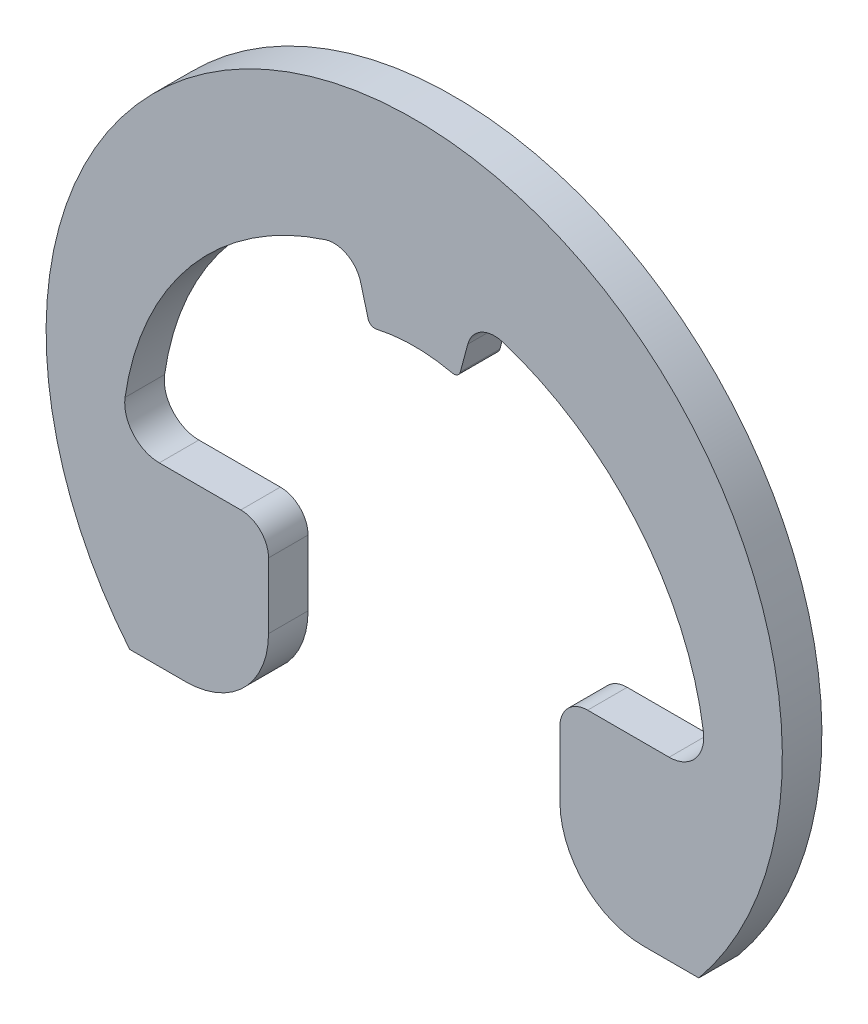
SolidWorks part; units mm, degrees
ref_plane "Front Plane" through (0, 0, 0) normal (0, 0, 1) x (1, 0, 0)
ref_plane "Top Plane" through (0, 0, 0) normal (0, 1, 0) x (1, 0, 0)
ref_plane "Right Plane" through (0, 0, 0) normal (1, 0, 0) x (0, 0, -1)
sketch "Sketch1" plane through (0, 0, 0) normal (0, 0, 1) x (1, 0, 0)
  circle A0 centre (0, 0) radius 8.375 construction
  circle A1 centre (0, 0) radius 3.9 construction
  point P3 (-8.375, 0)
  dimension "Ring OD" = 16.75
  dimension "ID" = 7.8
sketch "Sketch2" plane through (0, 0, 0) normal (0, 1, 0) x (1, 0, 0)
  line L0 (0, -0.45) -> (0, 0.45) construction
  line L1 (-8.375, -0.45) -> (0, -0.45) construction
  line L2 (-8.375, -0.45) -> (-8.375, 0.45) construction
  line L3 (-8.375, 0.45) -> (0, 0.45) construction
  point P2 (0, 0)
  dimension "Ring Thickness" = 0.9
sketch "Sketch3" plane through (0, 0, 0) normal (0, 1, 0) x (1, 0, 0)
  line L0 (-8.375, -0.45) -> (-8.375, 0.45)
  line L1 (0, 0.45) -> (0, -0.45)
  line L2 (-8.375, -0.45) -> (0, -0.45)
  line L3 (-8.375, 0.45) -> (0, 0.45)
revolve "Revolve1" add sketch "Sketch3" angle 360 about L1
sketch "Sketch4" plane through (0, 0, 0) normal (0, 0, 1) x (1, 0, 0)
  line L0 (1.0094, 3.7671) -> (1.7528, 6.5416) construction
  line L1 (-1.0094, 3.7671) -> (-1.7528, 6.5416) construction
  line L2 (-3.315, -2.0545) -> (-3.315, -5.3125)
  line L3 (3.315, -2.0545) -> (3.315, -5.3125)
  line L4 (-6.6465, -1.3) -> (-3.677, -1.3)
  line L5 (6.6465, -1.3) -> (3.677, -1.3)
  line L6 (-3.677, -1.3) -> (-3.315, -1.3)
  line L7 (-1.0094, 3.7671) -> (1.0094, 3.7671) construction
  line L8 (-8.375, 0) -> (0, 0) construction
  line L9 (-3.315, -5.3125) -> (-6.4744, -5.3125)
  line L10 (3.315, -5.3125) -> (6.4744, -5.3125)
  line L11 (-1.3811, 5.1544) -> (-1.0094, 3.7671)
  line L12 (1.3811, 5.1544) -> (1.0094, 3.7671)
  line L13 (-3.315, -1.3) -> (-3.315, -2.0545)
  line L14 (3.677, -1.3) -> (3.315, -1.3)
  line L15 (3.315, -1.3) -> (3.315, -2.0545)
  arc A0 (-1.3811, 5.1544) -> (-6.6465, -1.3) centre (0, -1.3472) ccw
  circle A2 centre (0, 0) radius 3.9 construction
  circle A3 centre (0, 0) radius 3.9 construction
  arc A4 (6.6465, -1.3) -> (1.7528, 6.5416) centre (0, 0) ccw construction
  arc A5 (-1.0094, 3.7671) -> (1.0094, 3.7671) centre (0, 0) cw
  arc A6 (-3.677, -1.3) -> (-3.315, -2.0545) centre (0, 0) ccw construction
  arc A7 (3.677, -1.3) -> (3.315, -2.0545) centre (0, 0) cw construction
  arc A8 (-1.7528, 6.5416) -> (-6.6465, -1.3) centre (0, 0) ccw construction
  circle A9 centre (0, 0) radius 8.375 construction
  arc A10 (6.4744, -5.3125) -> (-6.4744, -5.3125) centre (0, 0) ccw
  arc A11 (1.3811, 5.1544) -> (6.6465, -1.3) centre (0, -1.3472) cw
  point P2 (-1.3811, 5.1544)
  point P7 (0, 3.9)
  point P19 (1.3811, 5.1544)
  dimension "D1" = 6.7724
  dimension "D2" = 6.63
  dimension "D3" = 30
  dimension "D4" = 1.3
  dimension "D5" = 9.2125
extrude "Cut-Extrude1" cut sketch "Sketch4" against normal through all both and the other way through all flip side to cut
fillet "Fillet1" radius 0.63 4 edges at (-1.3811, 5.1544, 0) (1.3811, 5.1544, 0) (3.315, -1.3, 0) (-3.315, -1.3, 0)
fillet "Fillet2" radius 0.7875 2 edges at (6.6465, -1.3, 0) (-6.6465, -1.3, 0)
fillet "Fillet3" radius 1.89 2 edges at (3.315, -5.3125, 0) (-3.315, -5.3125, 0)
fillet "Fillet4" radius 0.1575 2 edges at (1.0094, 3.7671, 0) (-1.0094, 3.7671, 0)
sketch "Sketch5" plane through (0, 0, 0) normal (0, 0, 1) x (1, 0, 0)
  line L0 (-3.315, -2.0545) -> (-3.315, -5.3125) construction
  circle A2 centre (0, 0) radius 3.9 construction
  point P0 (-3.315, -2.0545)
equation "\"D1@Sketch4\"=(\"Ring OD@Sketch1\"+\"ID@Sketch1\")/3.625"
equation "\"D1@Fillet1\"=\"Ring Thickness@Sketch2\"*.7"
equation "\"D1@Fillet2\"=\"D1@Fillet1\"*1.25"
equation "\"D2@Sketch4\"=\"ID@Sketch1\"*.85"
equation "\"D4@Sketch4\"=\"ID@Sketch1\"/6"
equation "\"D5@Sketch4\"=\"Ring OD@Sketch1\"*.55"
equation "\"D1@Fillet3\"=\"D1@Fillet1\"*3"
equation "\"D1@Fillet4\"=\"D1@Fillet1\"*.25"
